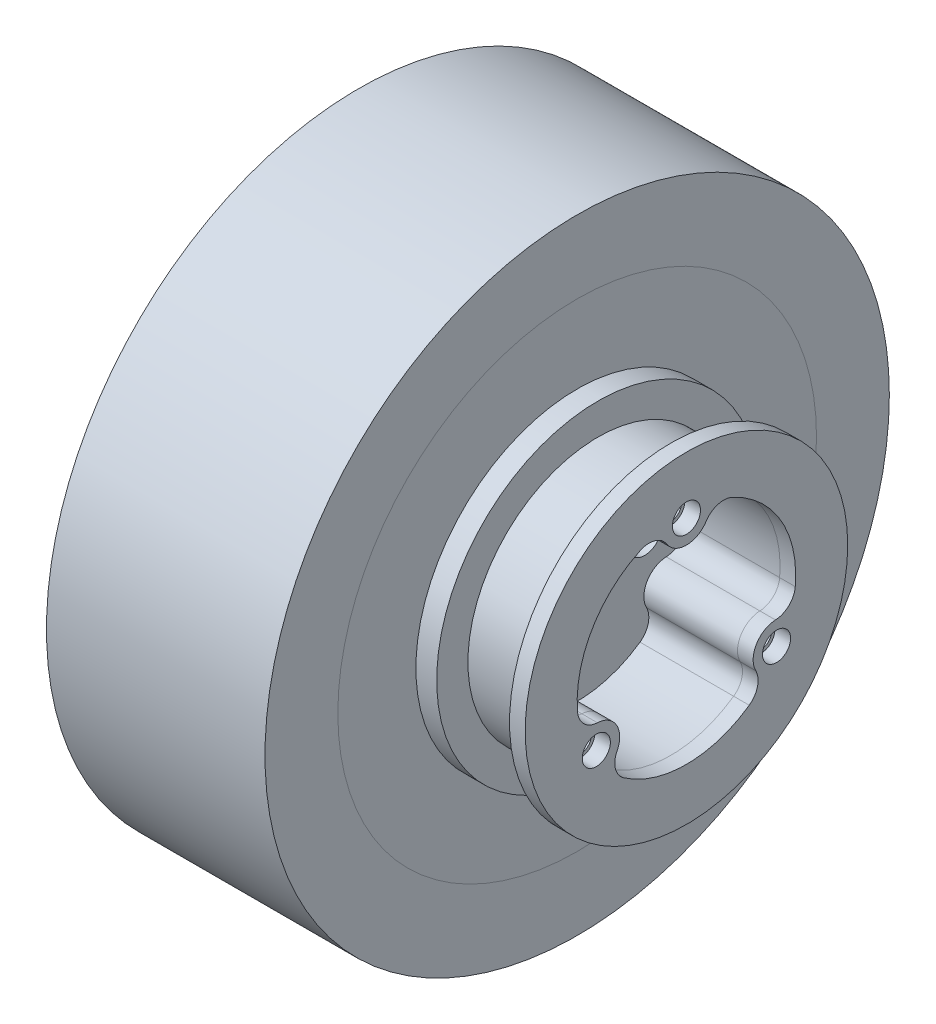
SolidWorks part; units mm, degrees
other "1"
material "6061 合金"
ref_plane "前视基准面" through (0, 0, 0) normal (0, 0, 1) x (1, 0, 0)
ref_plane "上视基准面" through (0, 0, 0) normal (0, 1, 0) x (1, 0, 0)
ref_plane "右视基准面" through (0, 0, 0) normal (1, 0, 0) x (0, 0, -1)
sketch "草图1" plane through (0, 0, 0) normal (1, 0, 0) x (0, 0, -1)
  circle A0 centre (0, 0) radius 21
  circle A1 centre (0, 0) radius 23
  dimension "D1" = 42
  dimension "D2" = 46
extrude "凸台-拉伸1" add sketch "草图1" along normal blind 17
sketch "草图2" plane through (17, 0, 0) normal (1, 0, 0) x (0, 0, -1)
  circle A0 centre (0, 0) radius 23
extrude "凸台-拉伸2" add sketch "草图2" along normal blind 4
sketch "草图3" plane through (21, 0, 0) normal (1, 0, 0) x (0, 0, -1)
  line L0 (0, 0) -> (0, 6.5) construction
  line L1 (0, 0) -> (6.5, 0) construction
  circle A1 centre (6.5, 0) radius 1.6
  circle A3 centre (-6.5, 0) radius 1.6
  dimension "D2" = 3.2
  dimension "D1" = 6.5
  dimension "D3" = 6.5
extrude "切除-拉伸1" cut sketch "草图3" against normal blind 4
sketch "草图5" plane through (21, 0, 0) normal (1, 0, 0) x (0, 0, -1)
  circle A0 centre (0, 0) radius 23
  circle A1 centre (0, 0) radius 30
  dimension "D1" = 46
  dimension "D2" = 60
extrude "凸台-拉伸4" add sketch "草图5" against normal up to surface (21 mm away) separate body up to face at (0, 0, -23)
sketch "草图6" plane through (21, 0, 0) normal (1, 0, 0) x (0, 0, -1)
  circle A0 centre (0, 0) radius 3.4925
  dimension "D1" = 6.985
extrude "切除-拉伸2" cut sketch "草图6" against normal blind 10
sketch "草图11" plane through (0, 0, 0) normal (0, 0, 1) x (1, 0, 0)
  line L0 (-990.1271, 36.75) -> (49009.8729, 36.75) construction
  line L1 (0, 30) -> (0, -30) construction
  line L2 (-1000, 0) -> (49000, 0) construction
  line L3 (-989.5, 28.25) -> (49010.5, 28.25) construction
  circle A0 centre (10.5, 36.75) radius 8.5
  point P10 (0, 0)
  dimension "D2" = 17
  dimension "D1" = 36.75
  dimension "D3" = 10.5
sketch "草图12" plane through (21, 0, 0) normal (1, 0, 0) x (0, 0, -1)
  circle A0 centre (0, 0) radius 12.5
  circle A1 centre (0, 0) radius 10.5
  dimension "D1" = 25
  dimension "D2" = 2
extrude "凸台-拉伸5" add sketch "草图12" along normal blind 9
sketch "草图13" plane through (21, 0, 0) normal (1, 0, 0) x (0, 0, -1)
  circle A0 centre (0, 0) radius 15.5
  circle A1 centre (0, 0) radius 12.5 construction
  circle A2 centre (0, 0) radius 12.5 construction
  circle A3 centre (0, 0) radius 12.5
  dimension "D1" = 3
extrude "凸台-拉伸6" add sketch "草图13" along normal blind 2
sketch "草图14" plane through (30, 0, 0) normal (1, 0, 0) x (0, 0, -1)
  line L0 (0, -1000) -> (0, 49000) construction
  circle A0 centre (0, 10) radius 2.25
  circle A1 centre (0, 0) radius 10 construction
  circle A2 centre (0, 0) radius 10.5 construction
  circle A3 centre (0, 0) radius 10.5 construction
  circle A4 centre (0, 0) radius 10.5
  circle A5 centre (8.6603, -5) radius 2.25
  circle A6 centre (-8.6603, -5) radius 2.25
  point P18 (0, 0)
  circle M2 centre (0, 0) radius 10.5
  dimension "D1" = 0.5
  dimension "D2" = 4.5
  dimension "D3" = 3
extrude "凸台-拉伸7" add sketch "草图14" against normal blind 10 contours A0 M2 | A4 A6 | A4 A5
fillet "圆角2" radius 2 6 edges at (25.5, -3.1941, -10.0024) (25.5, -7.0653, -7.7674) (25.5, -7.0653, 7.7674) (25.5, -3.1941, 10.0024) (25.5, 10.2594, 2.235) (25.5, 10.2594, -2.235)
sketch "草图15" plane through (30, 0, 0) normal (1, 0, 0) x (0, 0, -1)
  circle A0 centre (0, 10) radius 1.025
  circle A1 centre (8.6603, -5) radius 1.025
  circle A2 centre (-8.6603, -5) radius 1.025
  dimension "D1" = 2.05
extrude "切除-拉伸3" cut sketch "草图15" against normal blind 33
other "移动面1" face at (17, 0, -21) parameters "D1"=0.3
sketch "草图16" plane through (30, 0, 0) normal (1, 0, 0) x (0, 0, -1)
  circle A0 centre (0, 0) radius 15.5
  circle A1 centre (0, 10) radius 1.35
  circle A2 centre (8.6603, -5) radius 1.35
  circle A3 centre (-8.6603, -5) radius 1.35
  arc A4 (-2.235, 10.2594) -> (2.235, 10.2594) centre (0, 10) ccw
  arc A5 (10.0024, -3.1941) -> (7.7674, -7.0653) centre (8.6603, -5) ccw
  arc A6 (-7.7674, -7.0653) -> (-10.0024, -3.1941) centre (-8.6603, -5) ccw
  arc A7 (-7.7674, -7.0653) -> (7.7674, -7.0653) centre (0, 0) ccw
  arc A8 (10.0024, -3.1941) -> (2.235, 10.2594) centre (0, 0) ccw
  arc A9 (-2.235, 10.2594) -> (-10.0024, -3.1941) centre (0, 0) ccw
  dimension "D1" = 31
  dimension "D2" = 2.7
  dimension "D3" = 21
  dimension "D4" = 4.5
extrude "凸台-拉伸8" add sketch "草图16" along normal blind 1.5 separate body
fillet "圆角3" radius 2 6 edges at (30.75, 10.2594, 2.235) (30.75, -3.1941, 10.0024) (30.75, -7.0653, 7.7674) (30.75, -7.0653, -7.7674) (30.75, -3.1941, -10.0024) (30.75, 10.2594, -2.235)
